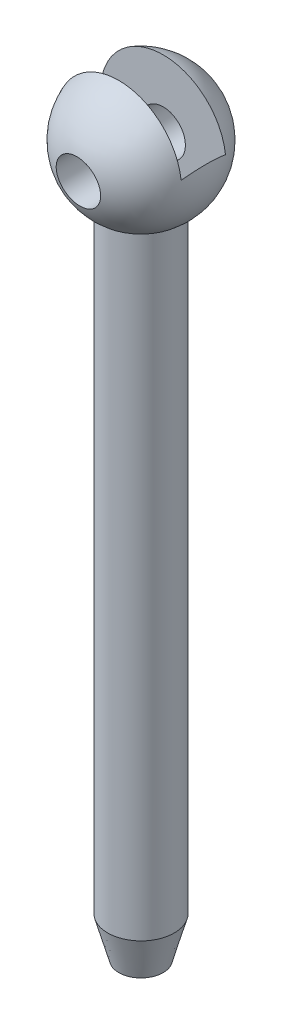
SolidWorks part; units mm, degrees
ref_plane "Plane1" through (0, 0, 0) normal (0, 0, 1) x (1, 0, 0)
ref_plane "Plane2" through (0, 0, 0) normal (0, 1, 0) x (1, 0, 0)
ref_plane "Plane3" through (0, 0, 0) normal (1, 0, 0) x (0, 0, -1)
other "Configuration Table"
sketch "Sketch1" plane through (0, 0, 0) normal (0, 0, 1) x (1, 0, 0)
  line L0 (0, -89) -> (5, -89)
  line L1 (5, -89) -> (7.5, -80)
  line L2 (0, 111) -> (0, -109) construction
  line L3 (7.5, -80) -> (7.5, 58.0096)
  line L4 (0, -89) -> (0, 86)
  arc A0 (7.5, 58.0096) -> (0, 86) centre (0, 71) ccw
  dimension "D7" = 30
  dimension "D1" = 5
  dimension "D2" = 5
  dimension "D3" = 89
  dimension "D5" = 7.5
revolve "Base-Revolve" add sketch "Sketch1" angle 360 about L2
sketch "Sketch2" plane through (0, 0, 0) normal (0, 0, 1) x (1, 0, 0)
  line L0 (0, 111) -> (0, -109) construction
  circle A0 centre (0, 70) radius 5
  dimension "D1" = 10
extrude "Cut-Extrude1" cut sketch "Sketch2" against normal mid plane 40
sketch "Sketch3" plane through (0, 0, 0) normal (0, 0, 1) x (1, 0, 0)
  line L0 (40, 110) -> (-40, 110)
  line L2 (8.2097, 64.2903) -> (40, 110)
  line L3 (-8.2097, 64.2903) -> (-40, 110)
  arc A0 (-8.2097, 64.2903) -> (8.2097, 64.2903) centre (0, 70) ccw
extrude "Cut-Extrude2" cut sketch "Sketch3" against normal mid plane 10
